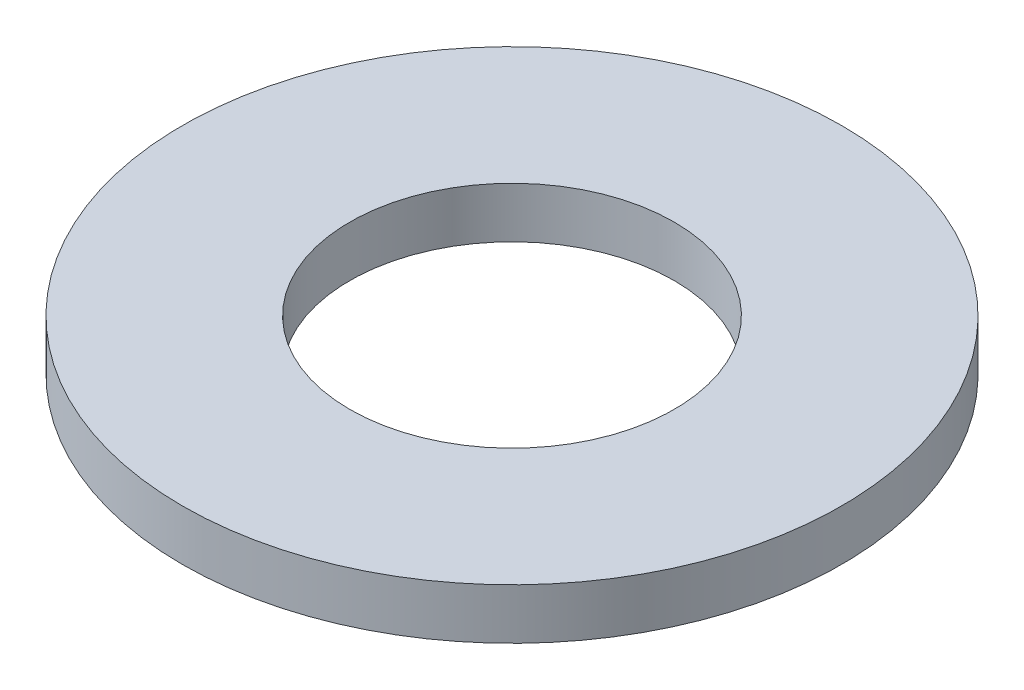
SolidWorks part; units mm, degrees
material "AISI 316 Stainless Steel Sheet (SS)"
ref_plane "Front Plane" through (0, 0, 0) normal (0, 0, 1) x (1, 0, 0)
ref_plane "Top Plane" through (0, 0, 0) normal (0, 1, 0) x (1, 0, 0)
ref_plane "Right Plane" through (0, 0, 0) normal (1, 0, 0) x (0, 0, -1)
sketch "Sketch1" plane through (0, 0, 0) normal (0, 1, 0) x (1, 0, 0)
  circle A0 centre (0, 0) radius 3.25
  circle A1 centre (0, 0) radius 1.6
  dimension "D1" = 6.5
  dimension "D2" = 3.2
extrude "Boss-Extrude1" add sketch "Sketch1" along normal blind 0.5
